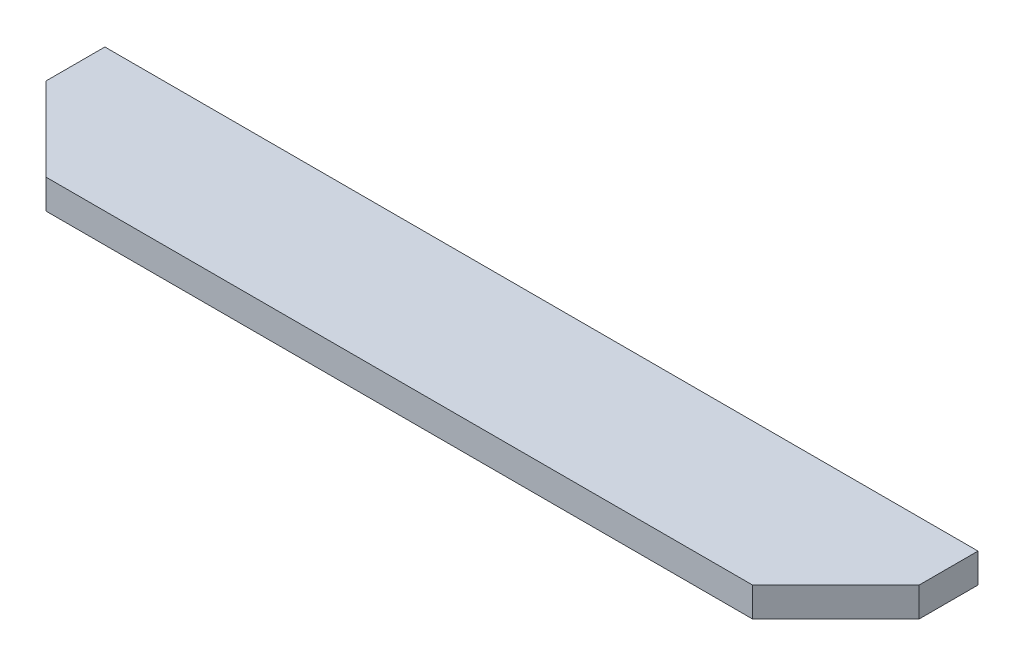
SolidWorks part; units mm, degrees
ref_plane "Front Plane" through (0, 0, 0) normal (0, 0, 1) x (1, 0, 0)
ref_plane "Top Plane" through (0, 0, 0) normal (0, 1, 0) x (1, 0, 0)
ref_plane "Right Plane" through (0, 0, 0) normal (1, 0, 0) x (0, 0, -1)
sketch "Sketch2" plane through (0, 0, 0) normal (0, 1, 0) x (1, 0, 0)
  line L0 (0, 0) -> (-120, 0)
  line L1 (-120, 0) -> (-134.1421, 14.1421)
  line L2 (-134.1421, 14.1421) -> (-134.1421, 24.1421)
  line L3 (0, 0) -> (14.1421, 14.1421)
  line L4 (14.1421, 14.1421) -> (14.1421, 24.1421)
  line L5 (14.1421, 24.1421) -> (-134.1421, 24.1421)
  dimension "D1" = 120
  dimension "D2" = 20
  dimension "D3" = 10
  dimension "D4" = 20
  dimension "D5" = 10
extrude "Boss-Extrude1" add sketch "Sketch2" along normal blind 5
